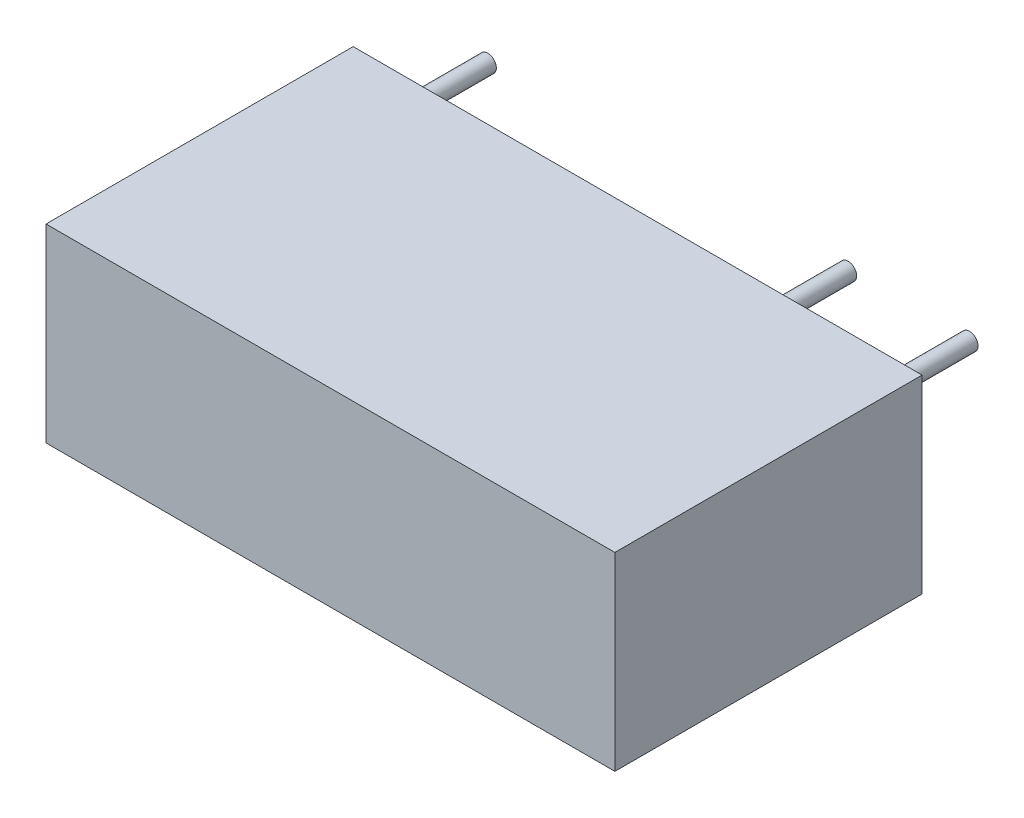
SolidWorks part; units mm, degrees
ref_plane "Спереди" through (0, 0, 0) normal (0, 0, 1) x (1, 0, 0)
ref_plane "Сверху" through (0, 0, 0) normal (0, 1, 0) x (1, 0, 0)
ref_plane "Справа" through (0, 0, 0) normal (1, 0, 0) x (0, 0, -1)
sketch "Эскиз1" plane through (0, 0, 0) normal (0, 0, 1) x (1, 0, 0)
  line L1 (-15, -5) -> (15, -5)
  line L2 (-15, -5) -> (-15, 5)
  line L3 (-15, 5) -> (15, 5)
  line L4 (15, -5) -> (15, 5)
  line L5 (-15, -5) -> (15, 5) construction
  line L6 (-15, 5) -> (15, -5) construction
  point P1 (0, 0)
  dimension "D1" = 30
  dimension "D2" = 10
extrude "Бобышка-Вытянуть1" add sketch "Эскиз1" along normal blind 16.2
sketch "Эскиз2" plane through (0, 0, 0) normal (0, 0, -1) x (-1, 0, 0)
  line L0 (15, 5) -> (15, -5) construction
  circle A0 centre (-13.5, 3.8) radius 0.45
  circle A1 centre (-7.1, 3.8) radius 0.45
  circle A2 centre (-10.3, -3.8) radius 0.45
  circle A3 centre (11.9, 3.8) radius 0.45
  circle A4 centre (11.9, -3.8) radius 0.45
  point P10 (0, 0)
  point P11 (0, 0)
  point P12 (0, 0)
  dimension "D1" = 0.9
  dimension "D2" = 3.1
  dimension "D3" = 3.8
  dimension "D4" = 3.8
  dimension "D5" = 3.2
  dimension "D6" = 3.2
  dimension "D7" = 19
extrude "Бобышка-Вытянуть2" add sketch "Эскиз2" along normal blind 4
